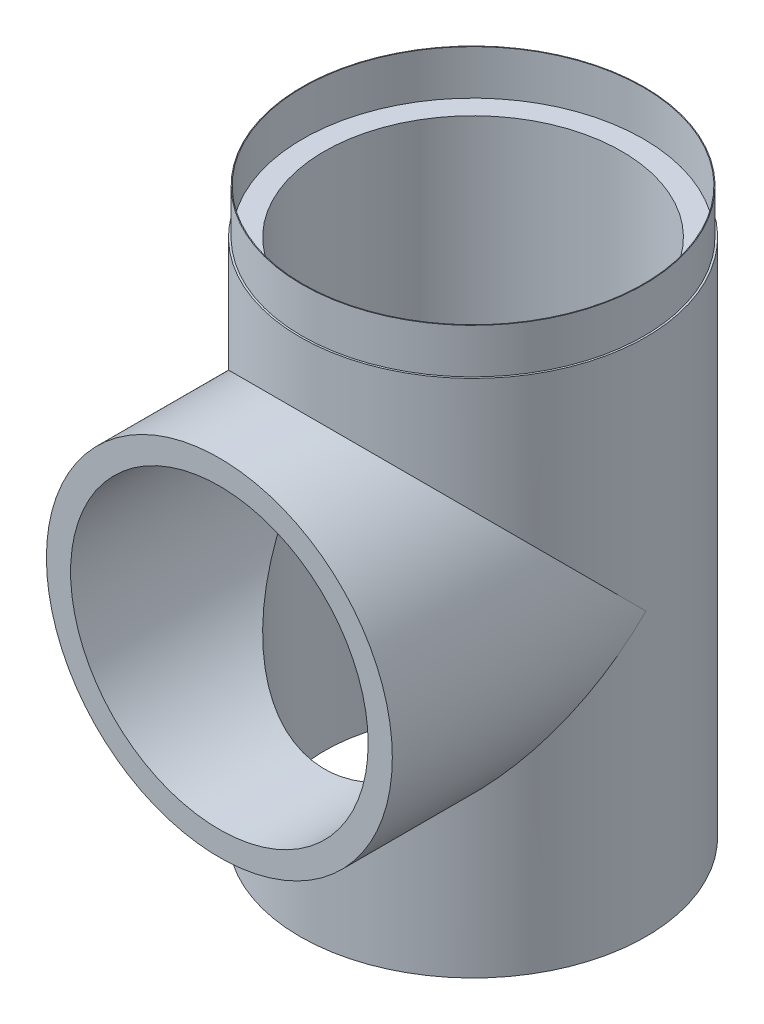
SolidWorks part; units mm, degrees
ref_plane "Спереди" through (0, 0, 0) normal (0, 0, 1) x (1, 0, 0)
ref_plane "Сверху" through (0, 0, 0) normal (0, 1, 0) x (1, 0, 0)
ref_plane "Справа" through (0, 0, 0) normal (1, 0, 0) x (0, 0, -1)
sketch "Эскиз1" plane through (0, 0, 0) normal (0, 1, 0) x (1, 0, 0)
  circle A0 centre (0, 0) radius 232.5
  circle A1 centre (0, 0) radius 200
  dimension "D1" = 465
  dimension "D2" = 400
extrude "Вытянуть1" add sketch "Эскиз1" along normal blind 698
sketch "Эскиз11" plane through (0, 698, 0) normal (0, 1, 0) x (1, 0, 0)
  circle A0 centre (0, 0) radius 230
  circle A2 centre (0, 0) radius 229
  dimension "D1" = 1
  dimension "D2" = 460
extrude "Бобышка-Вытянуть1" add sketch "Эскиз11" along normal blind 60
sketch "Эскиз12" plane through (0, 0, 0) normal (0, 0, 1) x (1, 0, 0)
  line L0 (0, 698) -> (0, 0) construction
  line L1 (-232.5, 0) -> (232.5, 0) construction
  circle A0 centre (0, 379) radius 232.5
  circle A1 centre (0, 379) radius 200
  dimension "D1" = 379
  dimension "D2" = 465
  dimension "D3" = 400
extrude "Бобышка-Вытянуть2" add sketch "Эскиз12" along normal blind 341
sketch "Эскиз13" plane through (0, 0, 0) normal (0, 0, 1) x (1, 0, 0)
  line L0 (0, 698) -> (0, 0) construction
  circle A0 centre (0, 379) radius 200
  circle A1 centre (0, 379) radius 200 construction
extrude "Вырез-Вытянуть1" cut sketch "Эскиз13" along normal blind 380
sketch "Эскиз14" plane through (0, 698, 0) normal (0, 1, 0) x (1, 0, 0)
  circle A0 centre (0, 0) radius 200
  dimension "D1" = 400
extrude "Вырез-Вытянуть2" cut sketch "Эскиз14" against normal blind 1000
